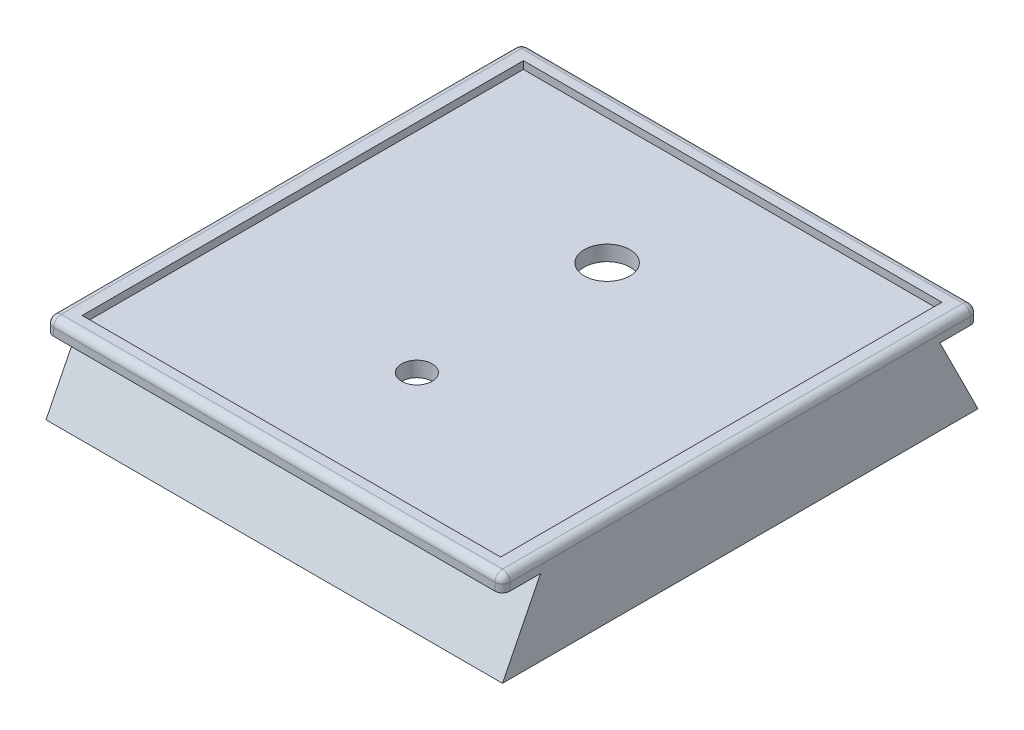
SolidWorks part; units mm, degrees
ref_plane "Front Plane" through (0, 0, 0) normal (0, 0, 1) x (1, 0, 0)
ref_plane "Top Plane" through (0, 0, 0) normal (0, 1, 0) x (1, 0, 0)
ref_plane "Right Plane" through (0, 0, 0) normal (1, 0, 0) x (0, 0, -1)
sketch "Sketch1" plane through (0, 0, 0) normal (0, 1, 0) x (1, 0, 0)
  line L1 (30, -31.25) -> (-30, -31.25)
  line L2 (30, -31.25) -> (30, 31.25)
  line L3 (30, 31.25) -> (-30, 31.25)
  line L4 (-30, -31.25) -> (-30, 31.25)
  line L5 (30, -31.25) -> (-30, 31.25) construction
  line L6 (30, 31.25) -> (-30, -31.25) construction
  point P0 (0, 0)
  dimension "D1" = 62.5
  dimension "D2" = 60
extrude "Boss-Extrude1" add sketch "Sketch1" along normal blind 10
sketch "Sketch2" plane through (30, 0, 0) normal (1, 0, 0) x (0, 0, -1)
  line L0 (31.25, 0) -> (26.25, 10)
  line L1 (-31.25, 10) -> (31.25, 10) construction
  line L2 (26.25, 10) -> (31.25, 10)
  line L3 (31.25, 10) -> (31.25, 0)
  dimension "D1" = 5
extrude "Cut-Extrude1" cut sketch "Sketch2" against normal through all
sketch "Sketch3" plane through (30, 0, 0) normal (1, 0, 0) x (0, 0, -1)
  line L0 (-31.25, 0) -> (-26.25, 10)
  line L1 (-31.25, 10) -> (26.25, 10) construction
  line L2 (-26.25, 10) -> (-31.25, 10)
  line L3 (-31.25, 10) -> (-31.25, 0)
  dimension "D1" = 5
extrude "Cut-Extrude2" cut sketch "Sketch3" against normal through all
sketch "Sketch4" plane through (0, 10, 0) normal (0, 1, 0) x (1, 0, 0)
  line L4 (-30, 31.25) -> (-30, -31.25)
  line L5 (30, 31.25) -> (-30, 31.25)
  line L6 (30, -31.25) -> (30, 31.25)
  line L7 (-30, -31.25) -> (30, -31.25)
  line L8 (-30, 31.25) -> (-30, -31.25)
  line L9 (30, 31.25) -> (-30, 31.25)
  line L10 (30, -31.25) -> (30, 31.25)
  line L11 (-30, -31.25) -> (30, -31.25)
  dimension "D1" = 0
extrude "Boss-Extrude2" add sketch "Sketch4" along normal blind 2
fillet "Fillet1" radius 1 4 edges at (30, 11, -31.25) (-30, 11, -31.25) (-30, 11, 31.25) (30, 11, 31.25)
fillet "Fillet2" radius 1 8 edges at (29.7071, 12, 30.9571) (0, 12, 31.25) (-29.7071, 12, 30.9571) (-30, 12, 0) (-29.7071, 12, -30.9571) (0, 12, -31.25) (29.7071, 12, -30.9571) (30, 12, 0)
sketch "Sketch5" plane through (0, 12, 0) normal (0, 1, 0) x (1, 0, 0)
  line L1 (27.5, -29) -> (-27.5, -29)
  line L2 (27.5, -29) -> (27.5, 29)
  line L3 (27.5, 29) -> (-27.5, 29)
  line L4 (-27.5, -29) -> (-27.5, 29)
  line L5 (27.5, -29) -> (-27.5, 29) construction
  line L6 (27.5, 29) -> (-27.5, -29) construction
  point P0 (0, 0)
  dimension "D1" = 55
  dimension "D2" = 58
extrude "Cut-Extrude3" cut sketch "Sketch5" against normal blind 1
sketch "Sketch6" plane through (0, 0, 0) normal (0, -1, 0) x (1, 0, 0)
  line L1 (-25, -25) -> (25, -25)
  line L2 (-25, -25) -> (-25, 25)
  line L3 (-25, 25) -> (25, 25)
  line L4 (25, -25) -> (25, 25)
  line L5 (-25, -25) -> (25, 25) construction
  line L6 (-25, 25) -> (25, -25) construction
  point P0 (0, 0)
  dimension "D1" = 50
  dimension "D2" = 50
extrude "Cut-Extrude4" cut sketch "Sketch6" against normal blind 9
sketch "Sketch7" plane through (0, 9, 0) normal (0, -1, 0) x (1, 0, 0)
  circle A0 centre (0, -12.5) radius 3
  dimension "D1" = 6
  dimension "D2" = 12.5
extrude "Cut-Extrude5" cut sketch "Sketch7" against normal blind 9
sketch "Sketch8" plane through (0, 11, 0) normal (0, 1, 0) x (1, 0, 0)
  circle A0 centre (0, -12.5) radius 2
  dimension "D1" = 12.5
  dimension "D2" = 4
extrude "Cut-Extrude6" cut sketch "Sketch8" against normal blind 10 contours A0
